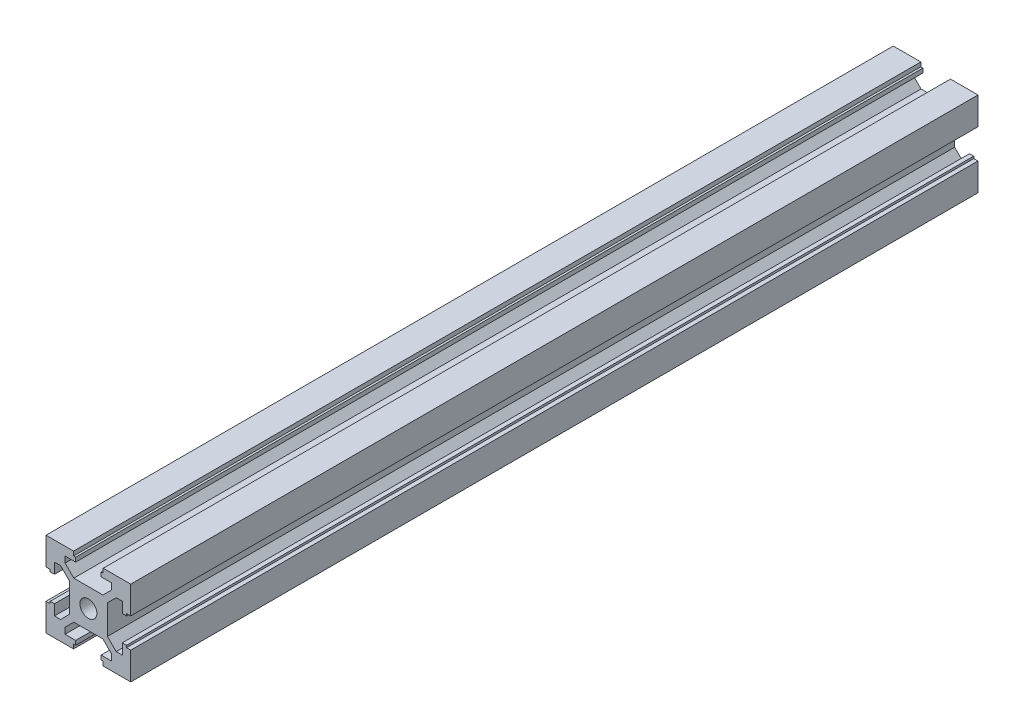
SolidWorks part; units mm, degrees
ref_plane "Front Plane" through (0, 0, 0) normal (0, 0, 1) x (1, 0, 0)
ref_plane "Top Plane" through (0, 0, 0) normal (0, 1, 0) x (1, 0, 0)
ref_plane "Right Plane" through (0, 0, 0) normal (1, 0, 0) x (0, 0, -1)
sketch "Sketch1" plane through (0, 0, 0) normal (0, 0, 1) x (1, 0, 0)
  line L0 (0, 10) -> (0, -4.5007) construction
  line L1 (-10, -10) -> (-3.5, -10)
  line L2 (-10, -10) -> (-10, -3.5)
  line L3 (-10, 10) -> (-3.5, 10)
  line L4 (10, -10) -> (10, -3.5)
  line L5 (-10, -10) -> (10, 10) construction
  line L6 (-10, 10) -> (10, -10) construction
  line L7 (-10, 0) -> (10, 0) construction
  line L8 (-3.5, 10) -> (-3.5, 9)
  line L9 (-3.44, -4.5007) -> (3.44, -4.5007)
  line L10 (-4.5007, -3.44) -> (-4.5007, 3.44)
  line L11 (-3.44, 4.5007) -> (3.44, 4.5007)
  line L12 (4.5007, -3.44) -> (4.5007, 3.44)
  line L13 (-10, -10) -> (10, 10) construction
  line L14 (-10, 10) -> (10, -10) construction
  line L15 (-3.5, 9) -> (-3, 9)
  line L16 (-3, 9) -> (-3, 8)
  line L17 (-3, 8) -> (-5.5, 8)
  line L18 (-5.5, 8) -> (-5.5, 6.5607)
  line L19 (-5.5, 6.5607) -> (-3.44, 4.5007)
  line L20 (3.5, 10) -> (10, 10)
  line L21 (3.5, 9) -> (3, 9)
  line L22 (5.5, 6.5607) -> (3.44, 4.5007)
  line L23 (5.5, 8) -> (5.5, 6.5607)
  line L24 (3, 8) -> (5.5, 8)
  line L25 (3, 9) -> (3, 8)
  line L26 (3.5, 10) -> (3.5, 9)
  line L27 (-3.5, 10) -> (3.5, 10) construction
  line L28 (5.5, -6.5607) -> (3.44, -4.5007)
  line L29 (5.5, -8) -> (5.5, -6.5607)
  line L30 (3, -8) -> (5.5, -8)
  line L31 (3, -9) -> (3, -8)
  line L32 (3.5, -9) -> (3, -9)
  line L33 (3.5, -10) -> (3.5, -9)
  line L34 (-3.5, -9) -> (-3, -9)
  line L35 (-5.5, -6.5607) -> (-3.44, -4.5007)
  line L36 (-5.5, -8) -> (-5.5, -6.5607)
  line L37 (-3, -8) -> (-5.5, -8)
  line L38 (-3, -9) -> (-3, -8)
  line L39 (-3.5, -10) -> (-3.5, -9)
  line L40 (-6.5607, -5.5) -> (-4.5007, -3.44)
  line L41 (-8, -5.5) -> (-6.5607, -5.5)
  line L42 (-8, -3) -> (-8, -5.5)
  line L43 (-10, -3.5) -> (-9, -3.5)
  line L44 (-9, -3) -> (-8, -3)
  line L45 (-9, -3.5) -> (-9, -3)
  line L46 (6.5607, -5.5) -> (4.5007, -3.44)
  line L47 (8, -5.5) -> (6.5607, -5.5)
  line L48 (8, -3) -> (8, -5.5)
  line L49 (9, -3) -> (8, -3)
  line L50 (9, -3.5) -> (9, -3)
  line L51 (10, -3.5) -> (9, -3.5)
  line L52 (-6.5607, 5.5) -> (-4.5007, 3.44)
  line L53 (-8, 5.5) -> (-6.5607, 5.5)
  line L54 (-8, 3) -> (-8, 5.5)
  line L55 (-9, 3) -> (-8, 3)
  line L56 (-9, 3.5) -> (-9, 3)
  line L57 (-10, 3.5) -> (-9, 3.5)
  line L58 (10, 3.5) -> (9, 3.5)
  line L59 (9, 3.5) -> (9, 3)
  line L60 (9, 3) -> (8, 3)
  line L61 (8, 3) -> (8, 5.5)
  line L62 (8, 5.5) -> (6.5607, 5.5)
  line L63 (6.5607, 5.5) -> (4.5007, 3.44)
  line L64 (10, 3.5) -> (10, 10)
  line L65 (-10, 3.5) -> (-10, 10)
  line L66 (-10, 3.5) -> (-10, -3.5) construction
  line L67 (10, 3.5) -> (10, -3.5) construction
  line L68 (3.5, -10) -> (10, -10)
  line L69 (-3.5, -10) -> (3.5, -10) construction
  circle A0 centre (0, 0) radius 2
  point P0 (0, 0)
  point P10 (0, 0)
  dimension "D10" = 4
  dimension "D1" = 20
  dimension "D2" = 14.5007
  dimension "D3" = 0.75
  dimension "D4" = 3.5
  dimension "D5" = 3
  dimension "D6" = 1
  dimension "D7" = 1
  dimension "D8" = 3.44
  dimension "D9" = 5.5
extrude "Boss-Extrude1" add sketch "Sketch1" along normal blind 200
